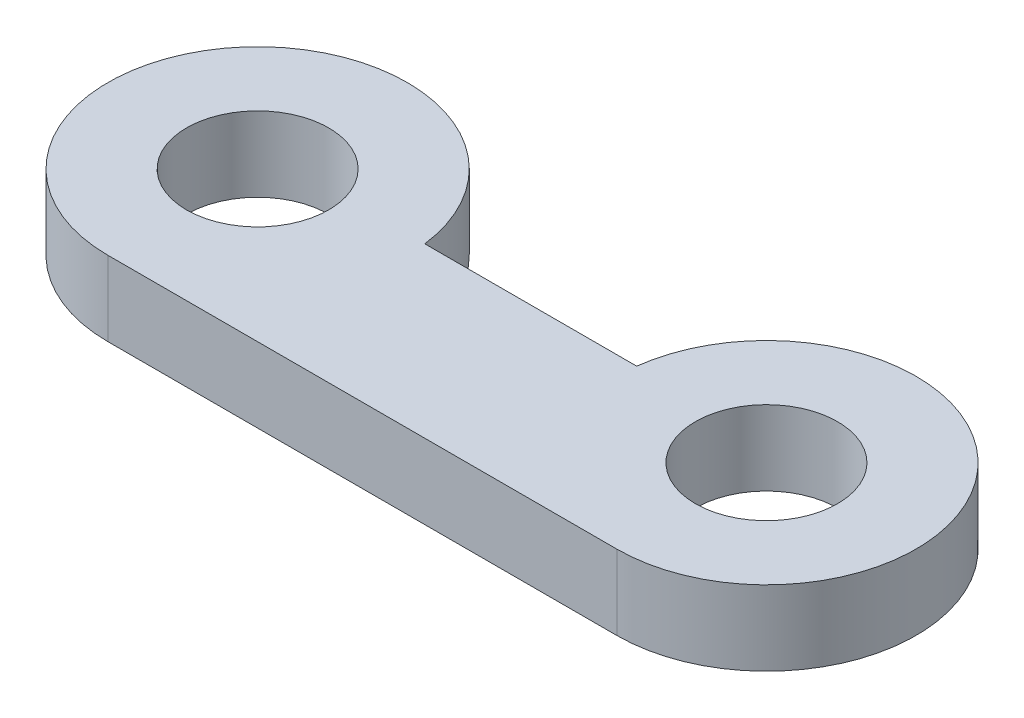
SolidWorks part; units mm, degrees
ref_plane "Front Plane" through (0, 0, 0) normal (0, 0, 1) x (1, 0, 0)
ref_plane "Top Plane" through (0, 0, 0) normal (0, 1, 0) x (1, 0, 0)
ref_plane "Right Plane" through (0, 0, 0) normal (1, 0, 0) x (0, 0, -1)
sketch "Sketch1" plane through (0, 0, 0) normal (0, 1, 0) x (1, 0, 0)
  line L0 (0, -138.2197) -> (0, 6772.7669) construction
  line L1 (6.8, 0) -> (-6.8, 0)
  line L2 (-2.8314, 4.5) -> (2.8314, 4.5)
  circle A0 centre (-6.8, 4) radius 1.9
  circle A1 centre (-6.8, 4) radius 4
  circle A2 centre (6.8, 4) radius 4
  circle A3 centre (6.8, 4) radius 1.9
  point P10 (0, 3.09)
  point P11 (0, 0)
  point P16 (0, 4.5)
  point P17 (0, 0)
  dimension "D1" = 3.8
  dimension "D2" = 8
  dimension "D3" = 4.5
  dimension "D4" = 6.8
extrude "Boss-Extrude1" add sketch "Sketch1" along normal blind 2 contours A1 A0 | L1 L0 L2 A1 | L0 L1 A2 L2 | A2 A3
